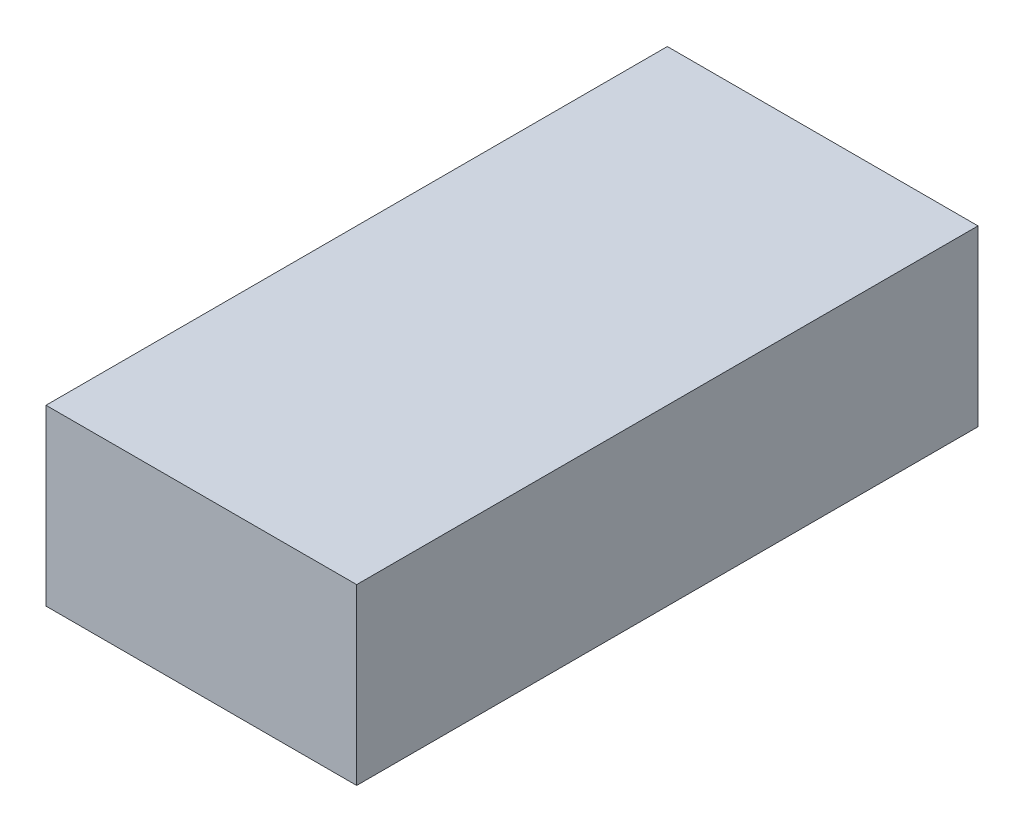
SolidWorks part; units mm, degrees
material "1.0553 (S355J0)"
ref_plane "Front Plane" through (0, 0, 0) normal (0, 0, 1) x (1, 0, 0)
ref_plane "Top Plane" through (0, 0, 0) normal (0, 1, 0) x (1, 0, 0)
ref_plane "Right Plane" through (0, 0, 0) normal (1, 0, 0) x (0, 0, -1)
sketch "Sketch1" plane through (0, 0, 0) normal (0, 0, 1) x (1, 0, 0)
  line L1 (-25, -14) -> (25, -14)
  line L2 (-25, -14) -> (-25, 14)
  line L3 (-25, 14) -> (25, 14)
  line L4 (25, -14) -> (25, 14)
  line L5 (-25, -14) -> (25, 14) construction
  line L6 (-25, 14) -> (25, -14) construction
  point P0 (0, 0)
  dimension "D1" = 50
  dimension "D2" = 28
extrude "Boss-Extrude1" add sketch "Sketch1" against normal blind 100
